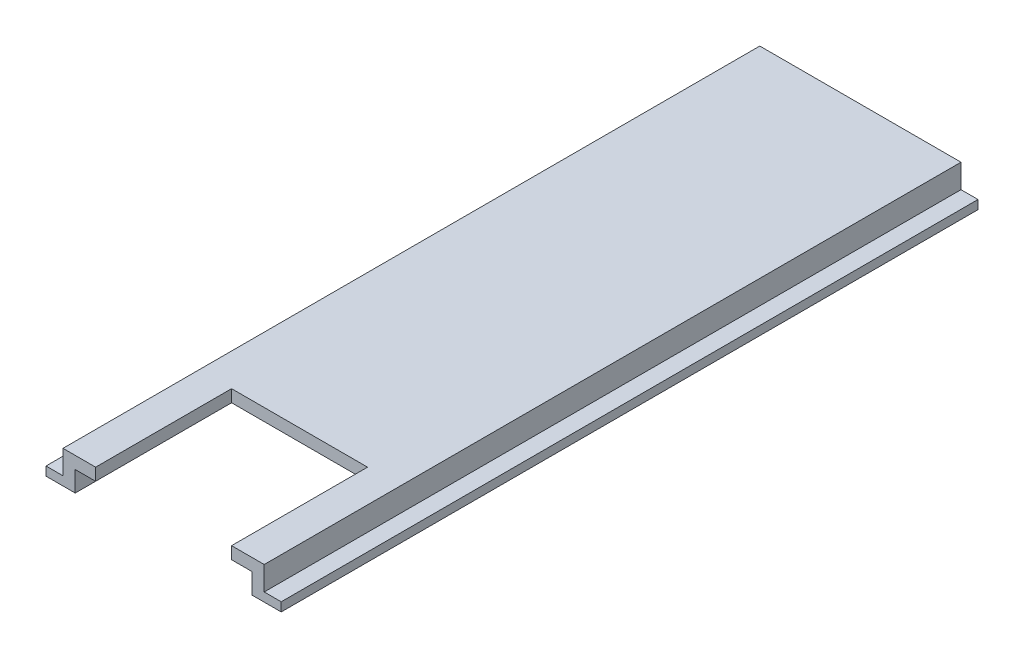
SolidWorks part; units mm, degrees
ref_plane "前视基准面" through (0, 0, 0) normal (0, 0, 1) x (1, 0, 0)
ref_plane "上视基准面" through (0, 0, 0) normal (0, 1, 0) x (1, 0, 0)
ref_plane "右视基准面" through (0, 0, 0) normal (1, 0, 0) x (0, 0, -1)
other "Configuration Table"
sketch "草图1" plane through (0, 0, 0) normal (0, 0, 1) x (1, 0, 0)
  line L0 (-16.5, 0) -> (-16.5, 1.5)
  line L1 (-16.5, 1.5) -> (-14, 1.5)
  line L2 (-14, 1.5) -> (-14, 5)
  line L3 (-14, 5) -> (16, 5)
  line L4 (16, 5) -> (16, 1.5)
  line L5 (16, 1.5) -> (18.5, 1.5)
  line L6 (18.5, 1.5) -> (18.5, 0)
  line L7 (18.5, 0) -> (14, 0)
  line L8 (14, 0) -> (14, 3)
  line L9 (14, 3) -> (-12, 3)
  line L10 (-12, 3) -> (-12, 0)
  line L11 (-12, 0) -> (-16.5, 0)
  point P3 (14, 1.5)
  dimension "D1" = 30
  dimension "D2" = 1.5
  dimension "D3" = 3.5
  dimension "D4" = 3.5
  dimension "D5" = 1.5
  dimension "D6" = 2
  dimension "D7" = 2.5
  dimension "D8" = 2.5
  dimension "D9" = 2
  dimension "D10" = 2
  dimension "D11" = 12
extrude "凸台-拉伸1" add sketch "草图1" along normal blind 56.5
sketch "草图2" plane through (0, 5, 0) normal (0, 1, 0) x (1, 0, 0)
  line L0 (16, -56.5) -> (-14, -56.5) construction
  line L1 (-9, -36.5) -> (11, -36.5)
  line L2 (-9, -36.5) -> (-9, -56.5)
  line L3 (-9, -56.5) -> (11, -56.5)
  line L4 (11, -36.5) -> (11, -56.5)
  line L5 (-14, -56.5) -> (-14, 0) construction
  dimension "D1" = 20
  dimension "D2" = 20
  dimension "D3" = 5
extrude "切除-拉伸1" cut sketch "草图2" against normal up to next
sketch "草图3" plane through (0, 0, 56.5) normal (0, 0, 1) x (1, 0, 0)
  line L0 (-16.3, 0) -> (-16.3, 1.3)
  line L1 (-16.5, 0) -> (-12, 0) construction
  line L2 (-16.3, 1.3) -> (-13.8, 1.3)
  line L3 (-13.8, 1.3) -> (-13.8, 4.8)
  line L4 (-13.8, 4.8) -> (15.8, 4.8)
  line L5 (15.8, 4.8) -> (15.8, 1.3)
  line L6 (15.8, 1.3) -> (18.3, 1.3)
  line L7 (18.3, 1.3) -> (18.3, 0)
  line L8 (14, 0) -> (18.5, 0) construction
  line L9 (18.3, 0) -> (18.5, 0)
  line L10 (18.5, 0) -> (18.5, 1.5)
  line L11 (18.5, 1.5) -> (16, 1.5)
  line L12 (16, 1.5) -> (16, 5)
  line L13 (16, 5) -> (-14, 5)
  line L14 (-14, 5) -> (-14, 1.5)
  line L15 (-14, 1.5) -> (-16.5, 1.5)
  line L16 (-16.5, 1.5) -> (-16.5, 0)
  line L17 (-16.5, 0) -> (-16.3, 0)
  dimension "D1" = 0.2
  dimension "D2" = 0.2
  dimension "D3" = 0.2
  dimension "D4" = 0.2
  dimension "D5" = 0.2
  dimension "D6" = 0.2
  dimension "D7" = 0.2
extrude "切除-拉伸2" cut sketch "草图3" against normal through all
sketch "草图4" plane through (0, 0, 0) normal (0, 0, -1) x (-1, 0, 0)
  line L1 (-23.9958, 10.25) -> (21.9958, 10.25)
  line L2 (-23.9958, 10.25) -> (-23.9958, -2.3049)
  line L3 (-23.9958, -2.3049) -> (21.9958, -2.3049)
  line L4 (21.9958, 10.25) -> (21.9958, -2.3049)
  line M1 (-18.3, 1.3) -> (-18.3, 0)
  line M2 (-18.3, 0) -> (-14, 0)
  line M3 (-14, 0) -> (-14, 3)
  line M4 (-14, 3) -> (12, 3)
  line M5 (12, 3) -> (12, 0)
  line M6 (12, 0) -> (16.3, 0)
  line M7 (16.3, 0) -> (16.3, 1.3)
  line M8 (16.3, 1.3) -> (13.8, 1.3)
  line M9 (13.8, 1.3) -> (13.8, 4.8)
  line M10 (13.8, 4.8) -> (-15.8, 4.8)
  line M11 (-15.8, 4.8) -> (-15.8, 1.3)
  line M12 (-15.8, 1.3) -> (-18.3, 1.3)
extrude "凸台-拉伸2" add sketch "草图4" along normal blind 46 contours M12 M1 M2 M3 M4 M5 M6 M7 M8 M9 M10 M11
